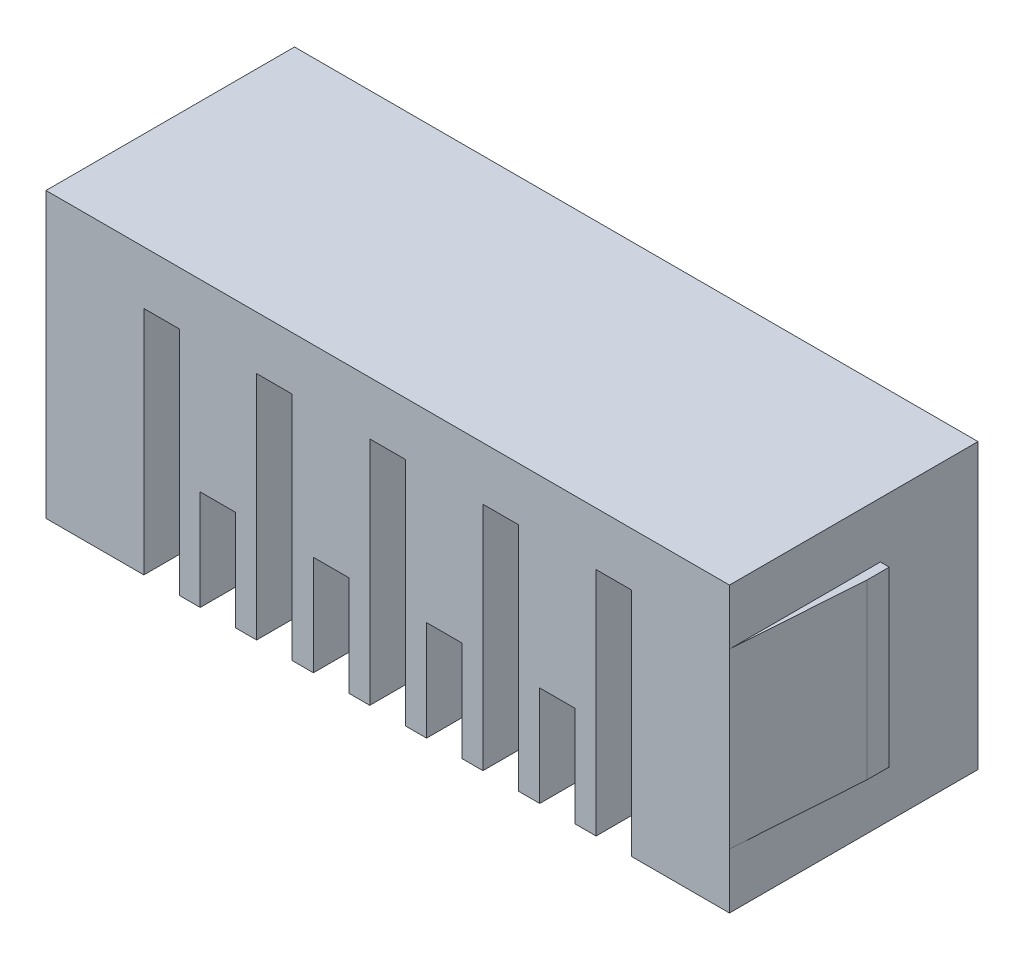
SolidWorks part; units mm, degrees
ref_plane "Front Plane" through (0, 0, 0) normal (0, 0, 1) x (1, 0, 0)
ref_plane "Top Plane" through (0, 0, 0) normal (0, 1, 0) x (1, 0, 0)
ref_plane "Right Plane" through (0, 0, 0) normal (1, 0, 0) x (0, 0, -1)
sketch "Sketch1" plane through (0, 0, 0) normal (0, 0, 1) x (1, 0, 0)
  line L1 (7.7, 3.2) -> (-7.7, 3.2)
  line L2 (7.7, 3.2) -> (7.7, -3.2)
  line L3 (7.7, -3.2) -> (-7.7, -3.2)
  line L4 (-7.7, 3.2) -> (-7.7, -3.2)
  line L5 (7.7, 3.2) -> (-7.7, -3.2) construction
  line L6 (7.7, -3.2) -> (-7.7, 3.2) construction
  point P0 (0, 0)
  dimension "D1" = 15.4
  dimension "D2" = 6.4
extrude "Boss-Extrude1" add sketch "Sketch1" along normal blind 5.6
sketch "Sketch2" plane through (0, -3.2, 0) normal (0, -1, 0) x (1, 0, 0)
  line L11 (4.695, 5.6) -> (5.495, 5.6)
  line L12 (4.695, 5.6) -> (4.695, 0.8)
  line L14 (5.495, 5.6) -> (5.495, 0.8)
  line L18 (2.145, 5.6) -> (2.145, 0.8)
  line L19 (2.145, 5.6) -> (2.945, 5.6)
  line L20 (2.945, 5.6) -> (2.945, 0.8)
  line L26 (-0.405, 5.6) -> (-0.405, 0.8)
  line L27 (-0.405, 5.6) -> (0.395, 5.6)
  line L28 (0.395, 5.6) -> (0.395, 0.8)
  line L34 (-2.955, 5.6) -> (-2.955, 0.8)
  line L35 (-2.955, 5.6) -> (-2.155, 5.6)
  line L36 (-2.155, 5.6) -> (-2.155, 0.8)
  line L38 (-7.7, 5.6) -> (7.7, 5.6) construction
  line L39 (-4.695, 5.6) -> (-5.495, 5.6)
  line L40 (-4.695, 5.6) -> (-4.695, 0.8)
  line L42 (-5.495, 5.6) -> (-5.495, 0.8)
  line L43 (4.225, 5.6) -> (3.425, 5.6)
  line L44 (4.225, 5.6) -> (4.225, 3.7)
  line L45 (4.225, 3.7) -> (3.425, 3.7)
  line L46 (3.425, 5.6) -> (3.425, 3.7)
  line L47 (3.425, 4.5) -> (3.425, 0.25) construction
  line L48 (4.225, 0.25) -> (4.225, 4.5) construction
  line L50 (4.695, 1.6) -> (4.695, 0.25) construction
  line L52 (1.675, 5.6) -> (1.675, 3.7)
  line L53 (1.675, 5.6) -> (0.875, 5.6)
  line L54 (0.875, 5.6) -> (0.875, 3.7)
  line L55 (1.675, 3.7) -> (0.875, 3.7)
  line L56 (-0.875, 5.6) -> (-0.875, 3.7)
  line L57 (-0.875, 5.6) -> (-1.675, 5.6)
  line L58 (-1.675, 5.6) -> (-1.675, 3.7)
  line L59 (-0.875, 3.7) -> (-1.675, 3.7)
  line L60 (-3.425, 5.6) -> (-3.425, 3.7)
  line L61 (-3.425, 5.6) -> (-4.225, 5.6)
  line L62 (-4.225, 5.6) -> (-4.225, 3.7)
  line L63 (-3.425, 3.7) -> (-4.225, 3.7)
  line L64 (-5.495, 0.8) -> (-4.695, 0.8)
  line L66 (-4.695, 1.6) -> (-5.495, 1.6) construction
  line L67 (-2.955, 0.8) -> (-2.155, 0.8)
  line L68 (-0.405, 0.8) -> (0.395, 0.8)
  line L69 (2.145, 0.8) -> (2.945, 0.8)
  line L70 (4.695, 0.8) -> (5.495, 0.8)
  dimension "D1" = 4
  dimension "D2" = 0
  dimension "D3" = 1.9
  dimension "D4" = 0.8
  dimension "D6" = 0
  dimension "D8" = 0.8
  dimension "D7" = 4
extrude "Cut-Extrude1" cut sketch "Sketch2" against normal blind 5.2
sketch "Sketch3" plane through (7.7, 0, 0) normal (1, 0, 0) x (0, 0, -1)
  line L0 (-2.1, -2.15) -> (-2.1, 2.15) construction
  line L1 (-5.6, 1.95) -> (-2.2, 1.95)
  line L2 (-5.6, 1.95) -> (-5.6, -1.95)
  line L3 (-5.6, -1.95) -> (-2.2, -1.95)
  line L4 (-2.2, 1.95) -> (-2.2, -1.95)
  line L5 (-2.1, 2.15) -> (-12.1, 2.15) construction
  line L6 (-2.1, -2.15) -> (-12.1, -2.15) construction
  line L7 (-5.6, -3.2) -> (-5.6, 3.2) construction
  dimension "D1" = 0.1
  dimension "D2" = 0.2
  dimension "D3" = 0.2
  dimension "D4" = 0
extrude "Boss-Extrude2" add sketch "Sketch3" along normal blind 0.2
sketch "Sketch4" plane through (0, 1.95, 0) normal (0, 1, 0) x (1, 0, 0)
  line L0 (7.9, -2.2) -> (7.9, -2.7) construction
  line L1 (7.9, -2.2) -> (7.9, -5.6) construction
  line L2 (7.9, -2.7) -> (7.7, -5.6)
  line L3 (7.9, -2.7) -> (7.9, -5.6)
  line L4 (7.9, -5.6) -> (7.7, -5.6)
  dimension "D1" = 0.5
extrude "Cut-Extrude2" cut sketch "Sketch4" against normal up to next
mirror "Mirror1" about plane through (0, 0, 0) normal (1, 0, 0) of "Cut-Extrude2", "Boss-Extrude2"
sketch "Sketch5" plane through (0, 0, 3.7) normal (0, 0, 1) x (1, 0, 0)
  line L0 (-3.425, 2) -> (-3.425, -3.2) construction
  line L1 (-4.225, 2) -> (-3.425, 2)
  line L2 (-4.225, 2) -> (-4.225, -0.945)
  line L3 (-4.225, -0.945) -> (-3.425, -0.945)
  line L4 (-3.425, 2) -> (-3.425, -0.945)
  line L5 (-0.875, 2) -> (-0.875, -3.2) construction
  line L6 (-1.675, 2) -> (-0.875, 2)
  line L7 (-1.675, 2) -> (-1.675, -0.945)
  line L8 (-1.675, -0.945) -> (-0.875, -0.945)
  line L9 (-0.875, 2) -> (-0.875, -0.945)
  line L10 (1.675, 2) -> (1.675, -3.2) construction
  line L11 (0.875, 2) -> (1.675, 2)
  line L12 (0.875, 2) -> (0.875, -0.945)
  line L13 (0.875, -0.945) -> (1.675, -0.945)
  line L14 (1.675, 2) -> (1.675, -0.945)
  line L15 (4.225, 2) -> (4.225, -3.2) construction
  line L16 (3.425, 2) -> (4.225, 2)
  line L17 (3.425, 2) -> (3.425, -0.945)
  line L18 (3.425, -0.945) -> (4.225, -0.945)
  line L19 (4.225, 2) -> (4.225, -0.945)
  circle A1 centre (-3.825, -1.475) radius 0.425 construction
  dimension "D1" = 0.53
extrude "Boss-Extrude3" add sketch "Sketch5" along normal up to surface (1.9 mm away) up to face at (-0.0014, -0.4909, 5.6)
